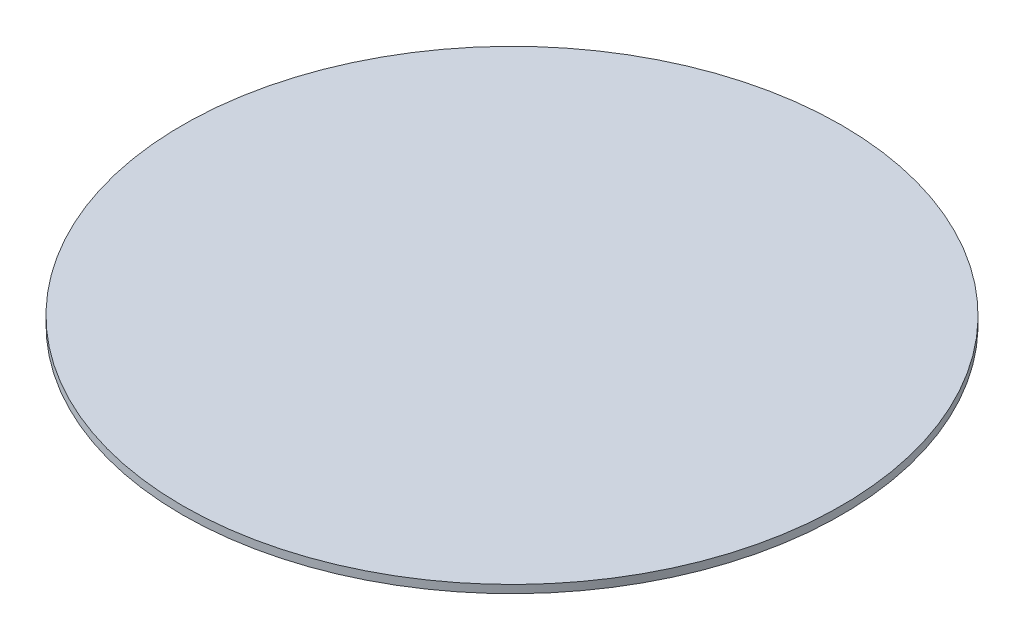
SolidWorks part; units mm, degrees
ref_plane "Plan de face" through (0, 0, 0) normal (0, 0, 1) x (1, 0, 0)
ref_plane "Plan de dessus" through (0, 0, 0) normal (0, 1, 0) x (1, 0, 0)
ref_plane "Plan de droite" through (0, 0, 0) normal (1, 0, 0) x (0, 0, -1)
sketch "Esquisse1" plane through (0, 0, 0) normal (0, 1, 0) x (1, 0, 0)
  circle A0 centre (0, 0) radius 41.25
extrude "Boss.-Extru.1" add sketch "Esquisse1" along normal blind 1
